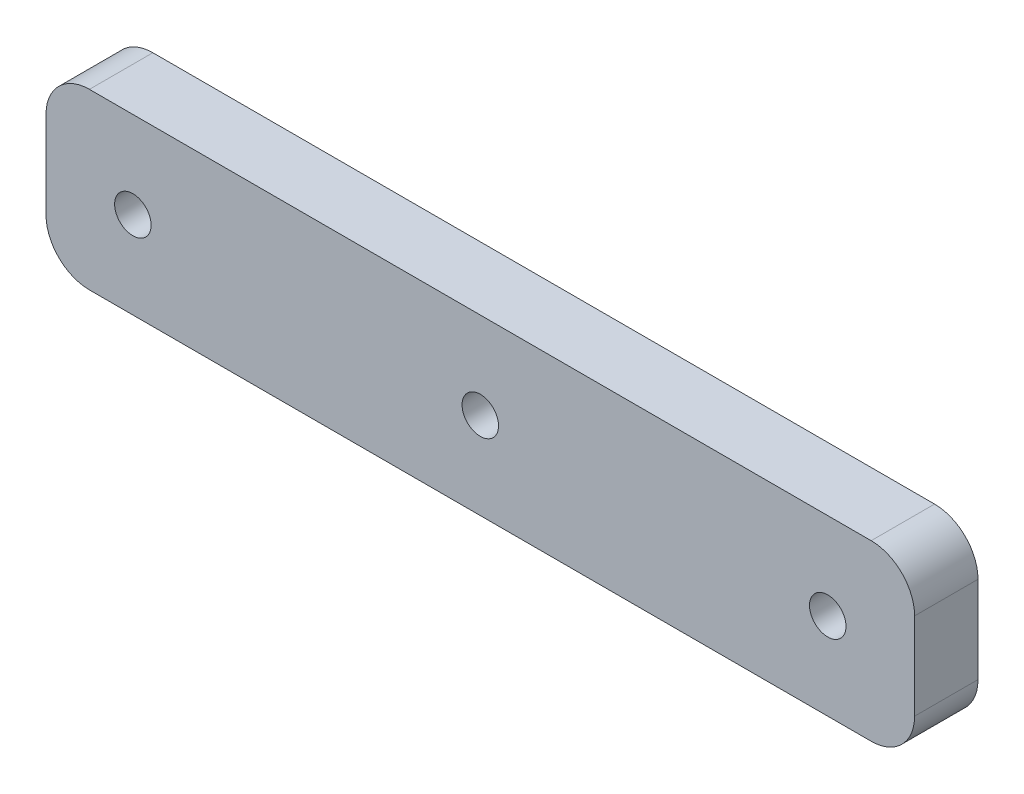
SolidWorks part; units mm, degrees
ref_plane "前视基准面" through (0, 0, 0) normal (0, 0, 1) x (1, 0, 0)
ref_plane "上视基准面" through (0, 0, 0) normal (0, 1, 0) x (1, 0, 0)
ref_plane "右视基准面" through (0, 0, 0) normal (1, 0, 0) x (0, 0, -1)
other "Configuration Table"
sketch "草图1" plane through (0, 0, 0) normal (0, 0, 1) x (1, 0, 0)
  line L1 (0, 0) -> (100, 0)
  line L2 (0, 0) -> (0, 20)
  line L3 (0, 20) -> (100, 20)
  line L4 (100, 0) -> (100, 20)
  dimension "D1" = 100
  dimension "D2" = 20
extrude "凸台-拉伸1" add sketch "草图1" along normal blind 7.3
sketch "草图2" plane through (0, 0, 7.3) normal (0, 0, 1) x (1, 0, 0)
  line L0 (0, 10) -> (100, 10) construction
  line L1 (0, 20) -> (0, 0) construction
  line L2 (100, 0) -> (100, 20) construction
  circle A0 centre (10, 10) radius 2.1
  circle A1 centre (50, 10) radius 2.1
  circle A2 centre (90, 10) radius 2.1
  dimension "D1" = 4.2
  dimension "D4" = 40
  dimension "D2" = 10
  dimension "D3" = 3
extrude "切除-拉伸1" cut sketch "草图2" against normal through all
fillet "圆角1" radius 5 4 edges at (100, 20, 3.65) (100, 0, 3.65) (0, 0, 3.65) (0, 20, 3.65)
